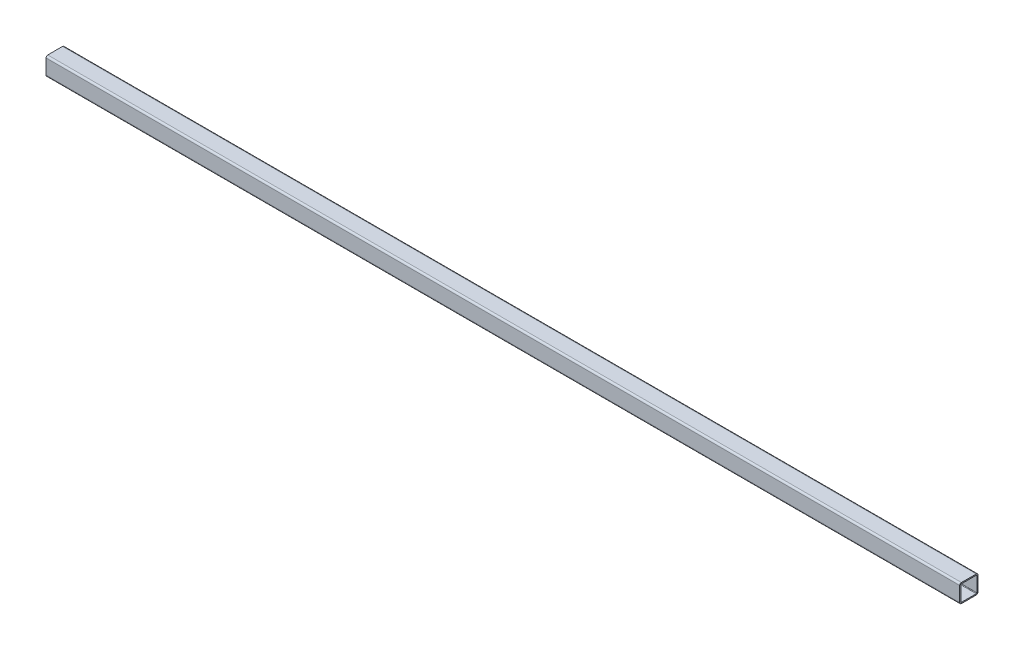
SolidWorks part; units mm, degrees
ref_plane "Спереди" through (0, 0, 0) normal (0, 0, 1) x (1, 0, 0)
ref_plane "Сверху" through (0, 0, 0) normal (0, 1, 0) x (1, 0, 0)
ref_plane "Справа" through (0, 0, 0) normal (1, 0, 0) x (0, 0, -1)
sketch "Эскиз1" plane through (0, 0, 0) normal (0, 0, 1) x (1, 0, 0)
  line L0 (-1000, 0) -> (1000, 0)
  point P4 (0, 0)
  dimension "D1" = 2000
other "Труба bxbxs гост8639-82 40 X 40 X 2.5(1)"
ref_plane "Плоскость1" through (-1000, 0, 0) normal (1, 0, 0) x (0, 1, 0)
sketch "Sketch1" plane through (-1000, 0, 0) normal (1, 0, 0) x (0, 1, 0)
  line L0 (-16.25, -17.5) -> (16.25, -17.5)
  line L1 (-17.5, -16.25) -> (-17.5, 16.25)
  line L2 (16.25, 17.5) -> (-16.25, 17.5)
  line L3 (17.5, 16.25) -> (17.5, -16.25)
  line L4 (-16.25, -20) -> (16.25, -20)
  line L5 (-20, -16.25) -> (-20, 16.25)
  line L6 (16.25, 20) -> (-16.25, 20)
  line L7 (20, 16.25) -> (20, -16.25)
  arc A0 (20, 16.25) -> (16.25, 20) centre (16.25, 16.25) ccw
  arc A1 (16.25, -20) -> (20, -16.25) centre (16.25, -16.25) ccw
  arc A2 (-20, -16.25) -> (-16.25, -20) centre (-16.25, -16.25) ccw
  arc A3 (-16.25, 20) -> (-20, 16.25) centre (-16.25, 16.25) ccw
  arc A4 (-16.25, 17.5) -> (-17.5, 16.25) centre (-16.25, 16.25) ccw
  arc A5 (17.5, 16.25) -> (16.25, 17.5) centre (16.25, 16.25) ccw
  arc A6 (16.25, -17.5) -> (17.5, -16.25) centre (16.25, -16.25) ccw
  arc A7 (-17.5, -16.25) -> (-16.25, -17.5) centre (-16.25, -16.25) ccw
  point P0 (-20, 0)
  point P1 (20, 0)
  point P2 (0, 20)
  point P3 (0, -20)
  point P4 (0, 0)
  point P5 (-20, -20)
  point P6 (20, -20)
  point P7 (20, 20)
  point P8 (-20, 20)
  point P33 (0, 0)
  dimension "D1" = 3.75
  dimension "Thickness" = 2.5
  dimension "V_leg" = 40
